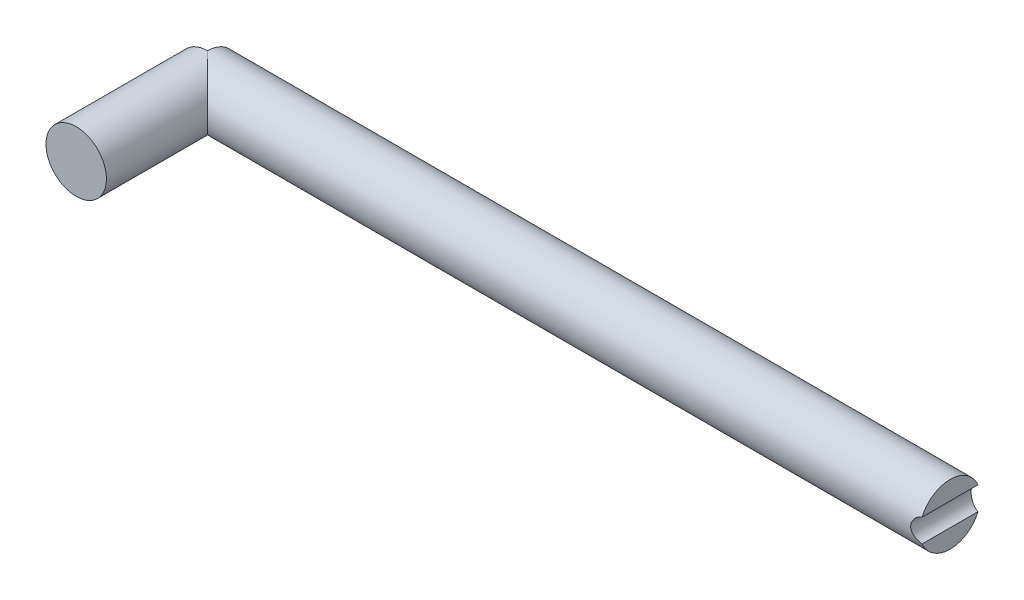
SolidWorks part; units mm, degrees
material "Legs"
ref_plane "Front Plane" through (0, 0, 0) normal (0, 0, 1) x (1, 0, 0)
ref_plane "Top Plane" through (0, 0, 0) normal (0, 1, 0) x (1, 0, 0)
ref_plane "Right Plane" through (0, 0, 0) normal (1, 0, 0) x (0, 0, -1)
sketch "Sketch1" plane through (0, 0, 0) normal (1, 0, 0) x (0, 0, -1)
  circle A0 centre (0, 0) radius 23
  dimension "D1" = 46
extrude "Length" add sketch "Sketch1" along normal blind 565
sketch "Sketch2" plane through (0, 0, 0) normal (0, 0, 1) x (1, 0, 0)
  circle A0 centre (0, 0) radius 23
  dimension "D1" = 46
extrude "Hip joint" add sketch "Sketch2" along normal blind 100
sketch "Sketch3" plane through (0, 0, 0) normal (0, 0, 1) x (1, 0, 0)
  circle A0 centre (567.0713, 0) radius 9.0714
extrude "Tibia axis" cut sketch "Sketch3" against normal up to next and the other way up to next
